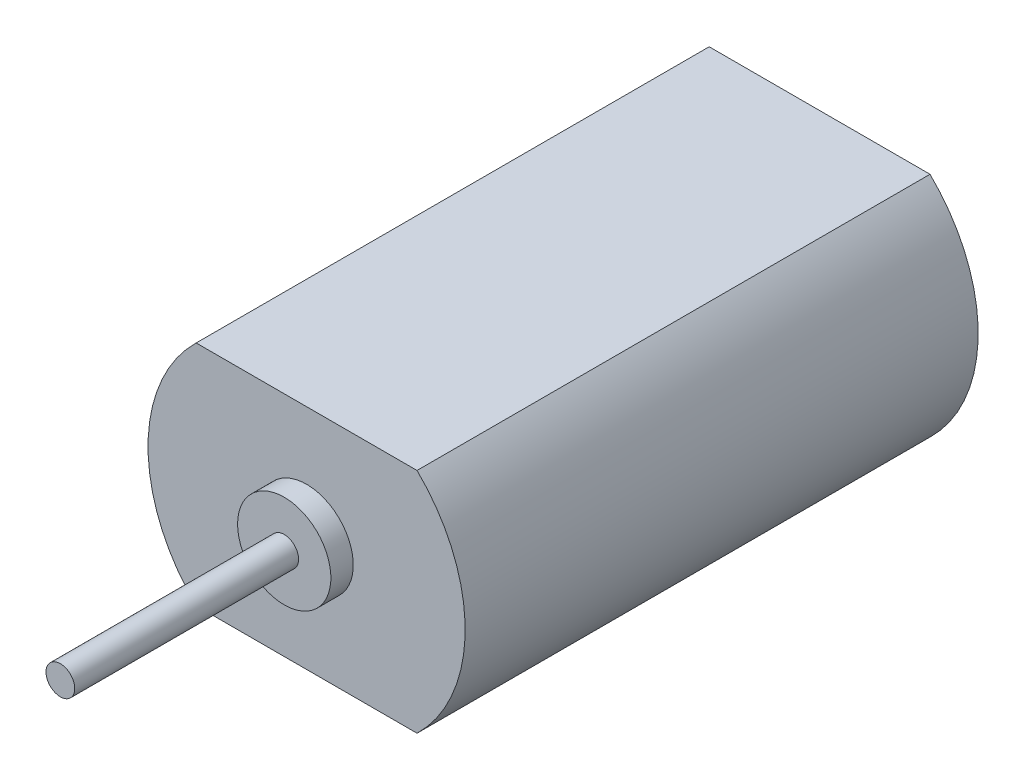
SolidWorks part; units mm, degrees
ref_plane "Front Plane" through (0, 0, 0) normal (0, 0, 1) x (1, 0, 0)
ref_plane "Top Plane" through (0, 0, 0) normal (0, 1, 0) x (1, 0, 0)
ref_plane "Right Plane" through (0, 0, 0) normal (1, 0, 0) x (0, 0, -1)
sketch "Sketch1" plane through (0, 0, 0) normal (0, 0, 1) x (1, 0, 0)
  line L0 (-7.5177, 7.747) -> (7.5177, 7.747)
  line L1 (7.5177, -7.747) -> (-7.5177, -7.747)
  circle A0 centre (0, 0) radius 10.795
  dimension "D1" = 15.494
  dimension "D2" = 21.59
extrude "Boss-Extrude1" add sketch "Sketch1" along normal blind 34.925 contours L0 A0 L1
sketch "Sketch2" plane through (0, 0, 34.925) normal (0, 0, 1) x (1, 0, 0)
  circle A0 centre (0, 0) radius 3.175
  dimension "D1" = 6.35
extrude "Boss-Extrude2" add sketch "Sketch2" along normal blind 1.524
sketch "Sketch3" plane through (0, 0, 36.449) normal (0, 0, 1) x (1, 0, 0)
  circle A0 centre (0, 0) radius 0.9779
  dimension "D1" = 1.9558
extrude "Boss-Extrude3" add sketch "Sketch3" along normal blind 15.24
sketch "Sketch4" plane through (0, 0, 0) normal (0, 0, -1) x (-1, 0, 0)
  circle A0 centre (0, 0) radius 0.9779
  circle A1 centre (0, 0) radius 0.9779 construction
extrude "Boss-Extrude4" add sketch "Sketch4" along normal blind 6.35
sketch "Sketch5" plane through (0, 0, 0) normal (0, 0, -1) x (-1, 0, 0)
  line L0 (-6.985, 0) -> (6.985, 0) construction
  line L1 (-8.001, 1.016) -> (-6.985, 1.016)
  line L2 (-8.001, 1.016) -> (-8.001, -1.016)
  line L3 (-8.001, -1.016) -> (-6.985, -1.016)
  line L4 (-6.985, 1.016) -> (-6.985, -1.016)
  line L5 (6.985, 1.016) -> (8.001, 1.016)
  line L6 (6.985, 1.016) -> (6.985, -1.016)
  line L7 (6.985, -1.016) -> (8.001, -1.016)
  line L8 (8.001, 1.016) -> (8.001, -1.016)
  dimension "D1" = 2.032
  dimension "D2" = 1.016
  dimension "D3" = 13.97
extrude "Boss-Extrude5" add sketch "Sketch5" along normal blind 2.032
